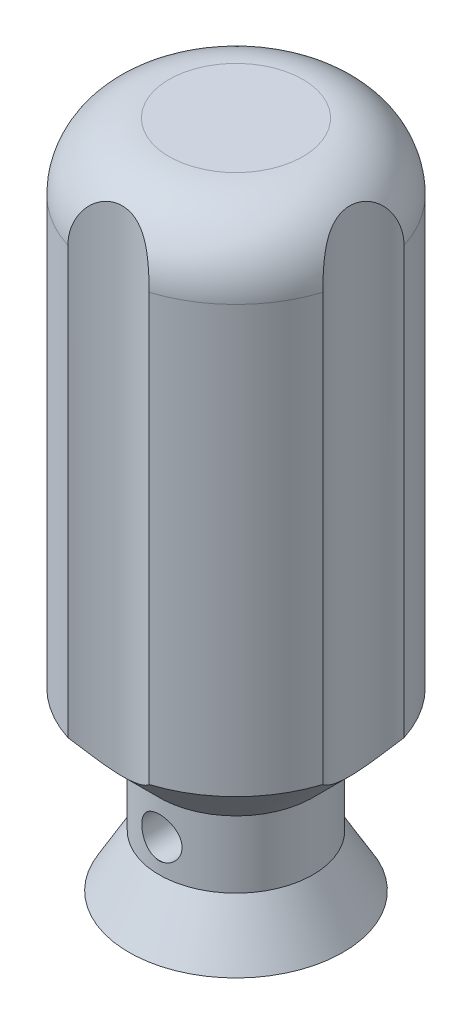
SolidWorks part; units mm, degrees
ref_plane "Front Plane" through (0, 0, 0) normal (0, 0, 1) x (1, 0, 0)
ref_plane "Top Plane" through (0, 0, 0) normal (0, 1, 0) x (1, 0, 0)
ref_plane "Right Plane" through (0, 0, 0) normal (1, 0, 0) x (0, 0, -1)
sketch "Sketch2" plane through (0, 0, 0) normal (0, 0, 1) x (1, 0, 0)
  line L0 (0, 0) -> (0, 100) construction
  line L1 (0, 0) -> (4, 0) construction
  line L2 (4, 0) -> (4, 30)
  line L3 (4, 0) -> (16, 0)
  line L5 (4, 30) -> (0, 30)
  line L6 (0, 30) -> (0, 100)
  line L7 (16, 0) -> (11.5, 7.7942)
  line L8 (11.5, 7.7942) -> (11.5, 17.7942)
  line L9 (11.5, 17.7942) -> (20, 26.2942)
  line L10 (20, 26.2942) -> (20, 90)
  line L11 (0, 100) -> (10, 100)
  arc A0 (20, 90) -> (10, 100) centre (10, 90) ccw
  dimension "D10" = 10
  dimension "D1" = 100
  dimension "D2" = 4
  dimension "D3" = 30
  dimension "D4" = 12
  dimension "D5" = 60
  dimension "D6" = 7.5
  dimension "D7" = 10
  dimension "D8" = 135
  dimension "D9" = 20
revolve "Revolve1" add sketch "Sketch2" angle 360 about L6
sketch "Sketch3" plane through (0, 0, 0) normal (0, -1, 0) x (1, 0, 0)
  line L0 (0, 27) -> (0, 0) construction
  circle A0 centre (0, 27) radius 10
  circle A1 centre (27, 0) radius 10
  circle A2 centre (0, -27) radius 10
  circle A3 centre (-27, 0) radius 10
  point P13 (0, 0)
  dimension "D1" = 20
  dimension "D4" = 27
  dimension "D2" = 27
  dimension "D5" = 27
  dimension "D3" = 4
extrude "Cut-Extrude1" cut sketch "Sketch3" against normal through all
hole_wizard "Ø6.0mm Dowel Hole1" positions "3DSketch1" profile "Sketch4" hole size "Ø6.0" standard "ANSI Metric" end condition through all
sketch3d "3DSketch1"
  point P0 (0.0306, 12.6473, 11.5)
sketch "Sketch4" plane through (0.0306, 12.6473, 11.5) normal (0, 1, 0) x (1, 0, -0.0027)
  line L0 (0, 0) -> (0, 31.1056)
  line L1 (0, 31.1056) -> (3, 31.1056)
  line L2 (3, 31.1056) -> (3, 0.025)
  line L3 (3, 0.025) -> (3.025, 0)
  line L5 (3.025, 0) -> (0, 0)
  line L6 (-3, 0.025) -> (-3.025, 0) construction
  line L11 (0, -6.35) -> (0, 107.95) construction
  dimension "Thru Hole Dia." = 6
  dimension "Thru Hole Depth" = 31.1056
  dimension "Near C'Sink Dia." = 6.05
  dimension "Near C'Sink Angle" = 90
